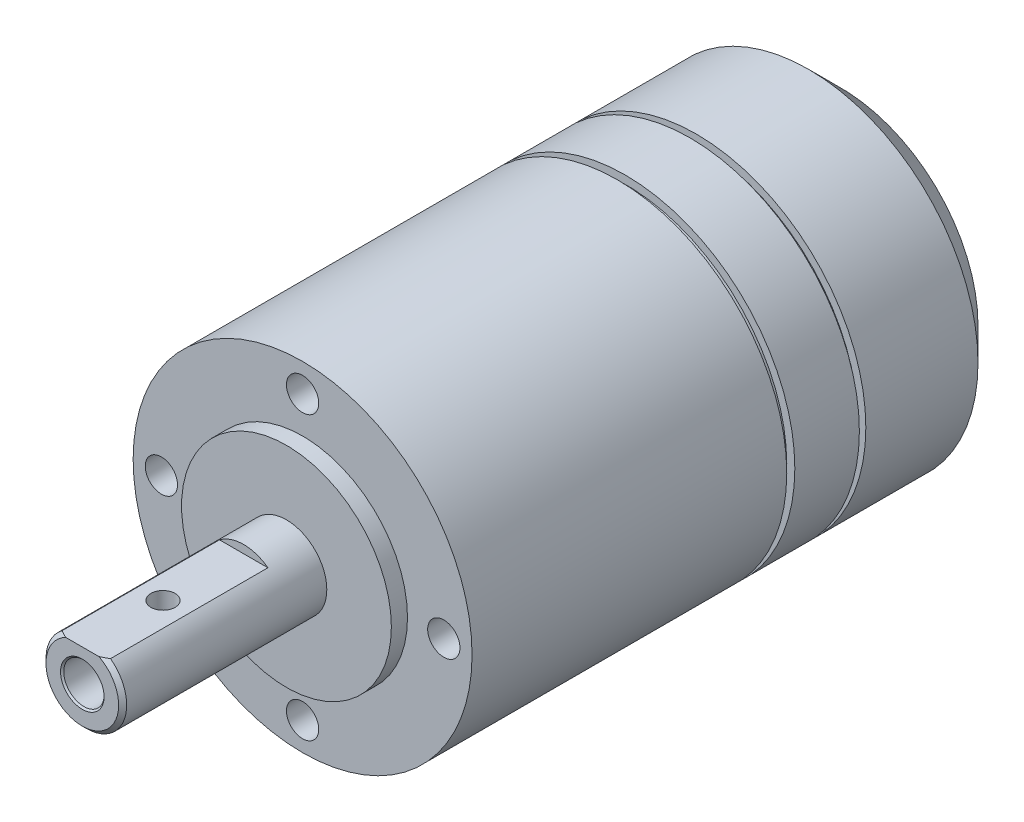
SolidWorks part; units mm, degrees
ref_plane "前视" through (0, 0, 0) normal (0, 0, 1) x (1, 0, 0)
ref_plane "上视" through (0, 0, 0) normal (0, 1, 0) x (1, 0, 0)
ref_plane "右视" through (0, 0, 0) normal (1, 0, 0) x (0, 0, -1)
sketch "草图1" plane through (0, 0, 0) normal (0, 0, 1) x (1, 0, 0)
  circle A0 centre (0, 0) radius 21
extrude "凸台-拉伸1" add sketch "草图1" along normal blind 39
sketch "草图2" plane through (0, 0, 39) normal (0, 0, 1) x (1, 0, 0)
  line L0 (0, 0) -> (25.4835, 0) construction
  line L1 (25.4835, 0) -> (-26.4657, 0) construction
  line L2 (-26.4657, 0) -> (0, 0) construction
  line L3 (0, 0) -> (0, -22.8369) construction
  line L4 (0, -22.8369) -> (0, 21.691) construction
  circle A0 centre (0, 0) radius 13
extrude "凸台-拉伸2" add sketch "草图2" along normal blind 2 contours A0
sketch "草图3" plane through (0, 0, 0) normal (1, 0, 0) x (0, 0, -1)
  line L0 (0, 0) -> (-61.4108, 0) construction
  line L1 (-61.4108, 0) -> (52.6783, 0) construction
sketch "草图4" plane through (0, 0, 41) normal (0, 0, 1) x (1, 0, 0)
  circle A0 centre (0, 0) radius 5
extrude "凸台-拉伸3" add sketch "草图4" along normal blind 25.3
chamfer "倒角1" distance 0.5 angle 45 1 edges at (5, 0, 66.3)
sketch "草图5" plane through (0, 0, 0) normal (1, 0, 0) x (0, 0, -1)
  line L0 (0, 0) -> (-61.4108, 0) construction
  line L1 (-35.4685, 0) -> (-50.7685, 0)
  line L2 (-50.7685, 0) -> (-50.7685, 8.3018)
  line L3 (-50.7685, 8.3018) -> (-50.7685, -7.1073)
ref_plane "基准面1" through (0, -5, 0) normal (0, 1, 0) x (1, 0, 0)
sketch "草图8" plane through (0, -5, 0) normal (0, 1, 0) x (1, 0, 0)
  line L0 (0, -66.3) -> (0, -56.3)
  line L1 (-4.5, -66.3) -> (4.5, -66.3) construction
  line L2 (0, 0) -> (0, -61.4108) construction
  circle A0 centre (0, -56.3) radius 1.5
sketch "草图11" plane through (0, -5, 0) normal (0, 1, 0) x (1, 0, 0)
  line L0 (0, -39) -> (0, -56.3)
  line L1 (-21, -39) -> (21, -39) construction
  circle A0 centre (0, -56.3) radius 1.5
extrude "切除-拉伸7" cut sketch "草图8" along normal blind 10.3 contours A0
hole_wizard "大小mm 暗销孔2" positions "草图15" profile "草图14" hole size "Ø5.0" standard "GB"
sketch "草图15" plane through (0, 0, 66.3) normal (0, 0, 1) x (1, 0, 0)
  point P1 (0, 0)
sketch "草图14" plane through (0, 0, 66.3) normal (1, 0, 0) x (0, -1, 0)
  line L0 (0, 0) -> (0, 11.5022)
  line L1 (0, 11.5022) -> (2.5, 10)
  line L2 (2.5, 10) -> (2.5, 0)
  line L5 (2.5, 0) -> (0, 0)
  line L10 (0, 11.5022) -> (-2.5, 10) construction
  line L11 (0, -6.35) -> (0, 107.95) construction
  dimension "孔直径" = 5
  dimension "孔深度" = 10
  dimension "导头角度" = 118
sketch "草图16" plane through (0, 0, 39) normal (0, 0, 1) x (1, 0, 0)
  circle A0 centre (0, 0) radius 17.5
  circle A1 centre (0, 0) radius 4
ref_plane "基准面2" through (0, 4, 0) normal (0, 1, 0) x (1, 0, 0)
sketch "草图17" plane through (0, 4, 0) normal (0, 1, 0) x (1, 0, 0)
  line L0 (0, -65.8) -> (-2, -65.8)
  line L2 (5, -65.8) -> (-5, -65.8) construction
  line L3 (-2, -65.8) -> (-2, -46.3)
  line L4 (-2, -46.3) -> (0, -46.3)
  line L5 (0, 0) -> (0, -61.4108) construction
  line L6 (0, -46.3) -> (2, -46.3)
  line L7 (2, -46.3) -> (2, -65.8)
  line L8 (2, -65.8) -> (0, -65.8)
  dimension "D1" = 19.5
  dimension "D2" = 19.5
extrude "切除-拉伸8" cut sketch "草图17" along normal blind 2
sketch "草图20" plane through (0, 0, 39) normal (0, 0, 1) x (1, 0, 0)
  line L0 (0, 0) -> (0, -27.0249)
  line L1 (0, -27.0249) -> (0, 30.093)
  line L2 (50, 0) -> (-50, 0) construction
  circle A0 centre (0, 17.5) radius 2
  circle A1 centre (0, 0) radius 17.5 construction
  circle A3 centre (17.5, 0) radius 2
  circle A4 centre (0, -17.5) radius 2
  circle A5 centre (-17.5, 0) radius 2
hole_wizard "大小mm 暗销孔1" positions "3D草图1" profile "草图21" hole size "Ø4.0" standard "GB"
sketch3d "3D草图1"
  point P0 (0, 17.5, 39)
  point P3 (-17.5, 0, 39)
  point P6 (17.5, 0, 39)
  point P9 (0, -17.5, 39)
sketch "草图21" plane through (0, 17.5, 39) normal (1, 0, 0) x (0, -1, 0)
  line L0 (0, 0) -> (0, 11.2017)
  line L1 (0, 11.2017) -> (2, 10)
  line L2 (2, 10) -> (2, 0)
  line L5 (2, 0) -> (0, 0)
  line L10 (0, 11.2017) -> (-2, 10) construction
  line L11 (0, -6.35) -> (0, 107.95) construction
  dimension "孔直径" = 4
  dimension "孔深度" = 10
  dimension "导头角度" = 118
sketch "草图22" plane through (0, 4, 0) normal (0, 1, 0) x (1, 0, 0)
  line L0 (-2, -65.8) -> (-2, -66.3)
  line L1 (-4.5, -66.3) -> (4.5, -66.3) construction
  line L2 (2, -65.8) -> (2, -66.3)
  line L3 (2, -66.3) -> (-2, -66.3)
sketch "草图23" plane through (0, 4, 0) normal (0, 1, 0) x (1, 0, 0)
  line L0 (-2, -65.8) -> (2, -65.8)
  line L1 (2, -65.8) -> (2, -66.3)
  line L2 (2, -66.3) -> (-2, -66.3)
  line L3 (2, -66.3) -> (-2, -66.3) construction
  line L4 (-2, -66.3) -> (-2, -65.8)
extrude "切除-拉伸12" cut sketch "草图23" along normal blind 2
sketch "草图24" plane through (0, 0, 0) normal (0, 0, -1) x (-1, 0, 0)
  circle A0 centre (0, 0) radius 20
extrude "凸台-拉伸4" add sketch "草图24" along normal blind 1
sketch "草图26" plane through (0, 0, -1) normal (0, 0, -1) x (-1, 0, 0)
  circle A0 centre (0, 0) radius 21
extrude "凸台-拉伸5" add sketch "草图26" along normal blind 8
sketch "草图27" plane through (0, 0, -9) normal (0, 0, -1) x (-1, 0, 0)
  circle A0 centre (0, 0) radius 20
extrude "凸台-拉伸6" add sketch "草图27" along normal blind 0.8 contours A0
sketch "草图28" plane through (0, 0, -9.8) normal (0, 0, -1) x (-1, 0, 0)
  circle A0 centre (0, 0) radius 21
extrude "凸台-拉伸7" add sketch "草图28" along normal blind 17.9
chamfer "倒角2" distance 4 angle 45 1 edges at (-21, 0, -27.7)
sketch "草图29" plane through (0, 0, -27.7) normal (0, 0, -1) x (-1, 0, 0)
  circle A0 centre (0, 0) radius 4
extrude "凸台-拉伸8" add sketch "草图29" along normal blind 4.4
sketch "草图30" plane through (0, 4, 0) normal (0, 1, 0) x (1, 0, 0)
  line L0 (0, -46.3) -> (3, -46.3)
  line L1 (-2, -46.3) -> (2, -46.3) construction
  line L2 (3, -46.3) -> (3, -66.3)
  line L3 (-4.5, -66.3) -> (4.5, -66.3) construction
  line L4 (0, -46.3) -> (-3, -46.3)
  line L5 (-3, -46.3) -> (-3, -66.3)
  line L6 (-3, -66.3) -> (3, -66.3)
extrude "切除-拉伸16" cut sketch "草图30" along normal blind 2
chamfer "倒角3" distance 0.2 angle 45 1 edges at (2.5, 0, 66.3)
